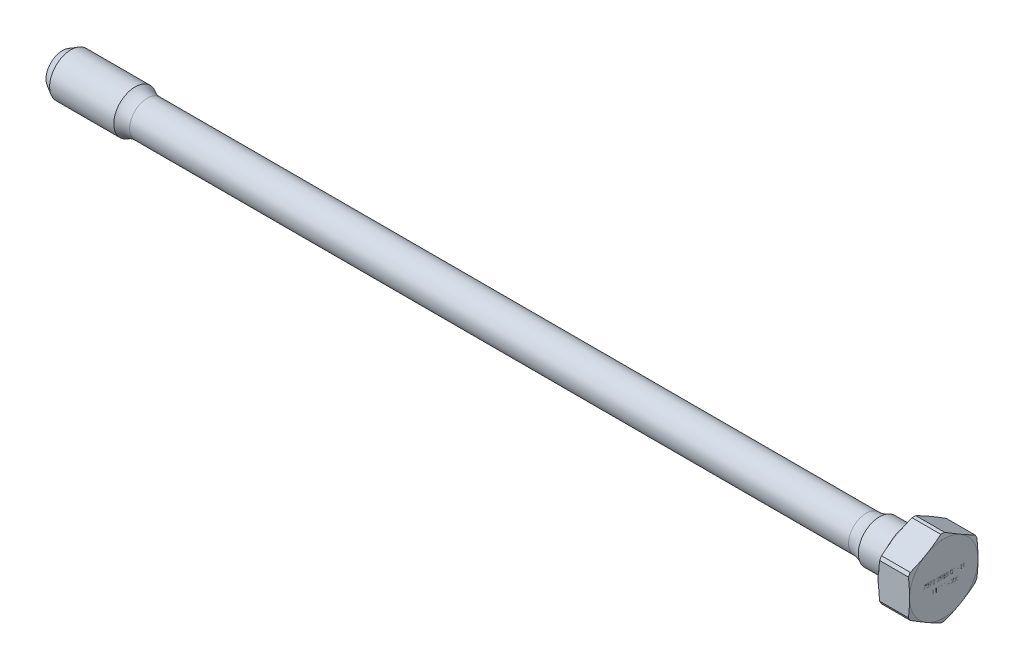
SolidWorks part; units mm, degrees
material "4340 H/T-Y"
ref_plane "Front Plane" through (0, 0, 0) normal (0, 0, 1) x (1, 0, 0)
ref_plane "Top Plane" through (0, 0, 0) normal (0, 1, 0) x (1, 0, 0)
ref_plane "Right Plane" through (0, 0, 0) normal (1, 0, 0) x (0, 0, -1)
sketch "Sketch1" plane through (0, 0, 0) normal (0, 0, 1) x (1, 0, 0)
  line L0 (8, 0) -> (6.7983, 2)
  line L1 (6.7983, 2) -> (3.4641, 2)
  line L2 (3.4641, 2) -> (0, 4)
  line L3 (0, 4) -> (0, 7.6906)
  line L4 (0, 7.6906) -> (4, 10)
  line L5 (4, 10) -> (34, 10)
  line L6 (8, 0) -> (412, 0)
  line L7 (39.6513, 8.25) -> (375.7064, 8.25)
  line L9 (382, 9.95) -> (395, 9.95)
  line L10 (397, 11.95) -> (397, 15.75)
  line L11 (397, 15.75) -> (397.5, 15.75)
  line L12 (397.5, 15.75) -> (397.5, 16)
  line L13 (397.5, 16) -> (398.0359, 18)
  line L14 (398.0359, 18) -> (411.4641, 18)
  line L15 (411.4641, 18) -> (412, 16)
  line L16 (412, 16) -> (412, 0)
  line L17 (412, 0) -> (8, 0) construction
  arc A0 (39.6513, 8.25) -> (34, 10) centre (39.6513, 18.25) cw
  arc A1 (375.7064, 8.25) -> (382, 9.95) centre (375.7064, 20.75) ccw
  arc A2 (397, 11.95) -> (395, 9.95) centre (395, 11.95) cw
  dimension "D13" = 10
  dimension "D16" = 12.5
  dimension "D23" = 2
  dimension "D1" = 412
  dimension "D2" = 0.5
  dimension "D3" = 397
  dimension "D4" = 4
  dimension "D5" = 8
  dimension "D6" = 59
  dimension "D7" = 30
  dimension "D8" = 8
  dimension "D9" = 4
  dimension "D10" = 30
  dimension "D11" = 20
  dimension "D12" = 16.5
  dimension "D14" = 34
  dimension "D15" = 19.9
  dimension "D17" = 382
  dimension "D18" = 31.5
  dimension "D19" = 36
  dimension "D20" = 32
  dimension "D21" = 15
  dimension "D22" = 75
revolve "Revolve1" add sketch "Sketch1" angle 360 about L17
cosmetic thread "Cosmetic Thread1" parameters "D2"=18
sketch "Sketch3" plane through (412, 0, 0) normal (1, 0, 0) x (0, 0, -1)
  line L1 (0, 18.4752) -> (-16, 9.2376)
  line L2 (-16, 9.2376) -> (-16, -9.2376)
  line L3 (-16, -9.2376) -> (0, -18.4752)
  line L4 (0, -18.4752) -> (16, -9.2376)
  line L5 (16, -9.2376) -> (16, 9.2376)
  line L6 (16, 9.2376) -> (0, 18.4752)
  circle A0 centre (0, 0) radius 16 construction
extrude "Cut-Extrude-Thin1" cut sketch "Sketch3" against normal up to surface (14.5 mm away) thin contours L2 L3 L4 L5 L6 L1
sketch "Sketch4" plane through (412, 0, 0) normal (-1, 0, 0) x (0, 0, -1)
  line L0 (-13.7374, 0) -> (13.8626, 0) construction
  line L1 (0, 17.7946) -> (0, -13.217) construction
  text T0 "7372 2988 01 - H\r\n 11111 - XX" font "Century Gothic" height 1.8
extrude "Cut-Extrude1" cut sketch "Sketch4" along normal blind 0.01
